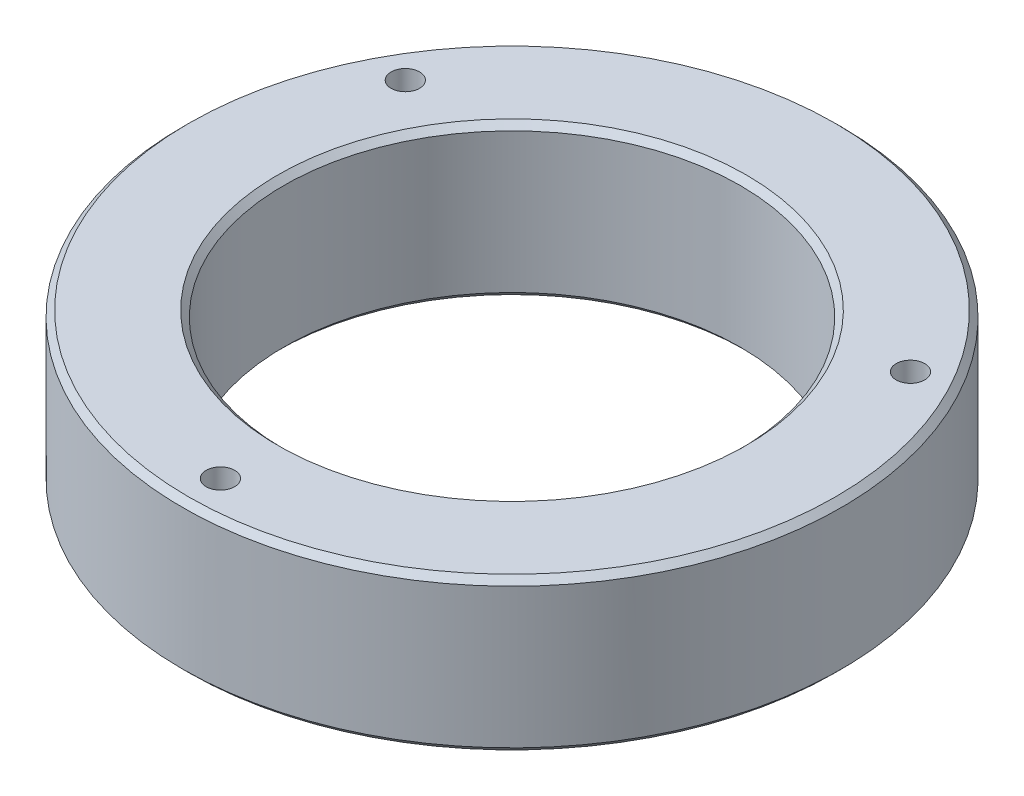
SolidWorks part; units mm, degrees
ref_plane "Front Plane" through (0, 0, 0) normal (1, 0, 0) x (0, 1, 0)
ref_plane "Top Plane" through (0, 0, 0) normal (0, 0, 1) x (0, 1, 0)
ref_plane "Right Plane" through (0, 0, 0) normal (0, 1, 0) x (-1, 0, 0)
sketch "Sketch1" plane through (0, 0, 0) normal (0, 0, 1) x (0, 1, 0)
  line L0 (-19.05, 82.5246) -> (19.05, 82.5246)
  line L1 (19.05, 82.5246) -> (19.05, 57.15)
  line L2 (19.05, 57.15) -> (-19.05, 57.15)
  line L3 (-19.05, 57.15) -> (-19.05, 82.5246)
  line L4 (-44.45, 0) -> (44.45, 0) construction
revolve "Revolve1" add sketch "Sketch1" angle 360 about L4
sketch "Sketch2" plane through (0, 0, 0) normal (0, 1, 0) x (-1, 0, 0)
  circle A0 centre (0, 73.025) radius 3.5687
extrude "Cut-Extrude2" cut sketch "Sketch2" along normal through all from offset 19.05
sketch "Sketch3" plane through (0, 0, 0) normal (0, 1, 0) x (-1, 0, 0)
  circle A0 centre (0, 73.025) radius 5.5626
extrude "Cut-Extrude4" cut sketch "Sketch3" along normal blind 9.652 from offset 19.05
sketch "Sketch4" plane through (0, 0, 0) normal (0, 1, 0) x (-1, 0, 0)
  circle A0 centre (-63.246, -36.5252) radius 3.5687
extrude "Cut-Extrude6" cut sketch "Sketch4" along normal through all from offset 19.05
sketch "Sketch5" plane through (0, 0, 0) normal (0, 1, 0) x (-1, 0, 0)
  circle A0 centre (-63.246, -36.5252) radius 5.5626
extrude "Cut-Extrude8" cut sketch "Sketch5" along normal blind 9.652 from offset 19.05
sketch "Sketch6" plane through (0, 0, 0) normal (0, 1, 0) x (-1, 0, 0)
  circle A0 centre (63.246, -36.5252) radius 3.5687
extrude "Cut-Extrude10" cut sketch "Sketch6" along normal through all from offset 19.05
sketch "Sketch7" plane through (0, 0, 0) normal (0, 1, 0) x (-1, 0, 0)
  circle A0 centre (63.246, -36.5252) radius 5.5626
extrude "Cut-Extrude12" cut sketch "Sketch7" along normal blind 9.652 from offset 19.05
sketch "Sketch8" plane through (0, 0, 0) normal (0, 1, 0) x (-1, 0, 0)
  circle A0 centre (-69.85, 0) radius 3.9687
extrude "Cut-Extrude14" cut sketch "Sketch8" along normal blind 25.4 from offset 19.05
sketch "Sketch9" plane through (0, 0, 0) normal (0, 1, 0) x (-1, 0, 0)
  circle A0 centre (69.85, 0) radius 3.9687
extrude "Cut-Extrude16" cut sketch "Sketch9" along normal blind 25.4 from offset 19.05
chamfer "Chamfer1" distance 1.524 angle 45 4 edges at (0, 19.05, -57.15) (0, -19.05, -57.15) (0, 19.05, -82.5246) (0, -19.05, -82.5246)
